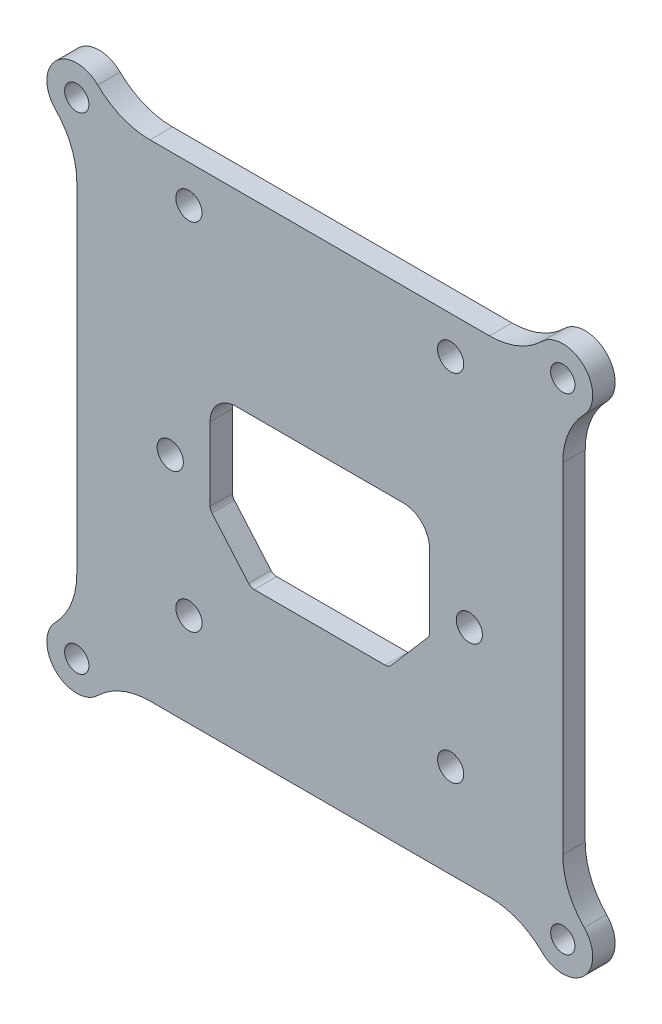
SolidWorks part; units mm, degrees
material "ABS"
ref_plane "Спереди" through (0, 0, 0) normal (0, 0, 1) x (1, 0, 0)
ref_plane "Сверху" through (0, 0, 0) normal (0, 1, 0) x (1, 0, 0)
ref_plane "Справа" through (0, 0, 0) normal (1, 0, 0) x (0, 0, -1)
sketch "Эскиз1" plane through (0, 0, 0) normal (0, 0, 1) x (1, 0, 0)
  line L1 (-32.5, -32.5) -> (32.5, -32.5)
  line L2 (-32.5, -32.5) -> (-32.5, 32.5)
  line L3 (-32.5, 32.5) -> (32.5, 32.5)
  line L4 (32.5, -32.5) -> (32.5, 32.5)
  line L5 (-32.5, -32.5) -> (32.5, 32.5) construction
  line L6 (-32.5, 32.5) -> (32.5, -32.5) construction
  circle A0 centre (-32.5, 32.5) radius 1.625
  arc A1 (-28.5, 32.5) -> (-32.5, 28.5) centre (-32.5, 32.5) ccw
  circle A2 centre (32.5, 32.5) radius 1.625
  arc A3 (32.5, 28.5) -> (28.5, 32.5) centre (32.5, 32.5) ccw
  circle A4 centre (32.5, -32.5) radius 1.625
  arc A5 (28.5, -32.5) -> (32.5, -28.5) centre (32.5, -32.5) ccw
  circle A6 centre (-32.5, -32.5) radius 1.625
  arc A7 (-32.5, -28.5) -> (-28.5, -32.5) centre (-32.5, -32.5) ccw
  point P0 (0, 0)
  point P20 (0, 0)
  dimension "D2" = 3.25
  dimension "D3" = 8
  dimension "D1" = 65
  dimension "D4" = 4
extrude "Бобышка-Вытянуть1" add sketch "Эскиз1" along normal blind 3 contours A6 L1 A4 L4 A2 L3 A0 L2 | L3 A1 L2 A0 | L4 A3 L3 A2 | L1 A5 L4 A4 | L2 A7 L1 A6
fillet "Скругление1" radius 10 8 edges at (-28.5, -32.5, 1.5) (-32.5, -28.5, 1.5) (-28.5, 32.5, 1.5) (-32.5, 28.5, 1.5) (28.5, 32.5, 1.5) (32.5, 28.5, 1.5) (32.5, -28.5, 1.5) (28.5, -32.5, 1.5)
sketch "Эскиз3" plane through (0, 0, 0) normal (0, 0, -1) x (-1, 0, 0)
  line L0 (0, 32.5) -> (0, -32.5) construction
  line L1 (22.702, 32.5) -> (-22.702, 32.5) construction
  line L2 (22.702, -32.5) -> (-22.702, -32.5) construction
  line L3 (-31.8936, 27.5) -> (26.7306, 27.5) construction
  circle A0 centre (-17.5, 27.5) radius 1.75
  circle A1 centre (17.5, 27.5) radius 1.75
  dimension "D1" = 3.5
  dimension "D2" = 17.5
  dimension "D3" = 27.5
extrude "Вырез-Вытянуть1" cut sketch "Эскиз3" against normal blind 10
sketch "Эскиз4" plane through (0, 0, 0) normal (0, 0, -1) x (-1, 0, 0)
  line L0 (0, 32.5) -> (0, -32.5) construction
  line L1 (22.702, 32.5) -> (-22.702, 32.5) construction
  line L2 (22.702, -32.5) -> (-22.702, -32.5) construction
  line L3 (-25.8899, -2.6153) -> (17.0132, -2.6153) construction
  circle A0 centre (-20, -2.6153) radius 1.75
  circle A1 centre (20, -2.6153) radius 1.75
  dimension "D1" = 3.5
  dimension "D2" = 20
extrude "Вырез-Вытянуть2" cut sketch "Эскиз4" against normal blind 10
sketch "Эскиз5" plane through (0, 0, 3) normal (0, 0, 1) x (1, 0, 0)
  line L0 (0, 32.5) -> (0, -32.5) construction
  line L1 (-22.702, 32.5) -> (22.702, 32.5) construction
  line L2 (-22.702, -32.5) -> (22.702, -32.5) construction
  line L3 (-29.8417, -20) -> (25.7956, -20) construction
  circle A0 centre (-17.5, -20) radius 1.75
  circle A1 centre (17.5, -20) radius 1.75
  dimension "D1" = 3.5
  dimension "D2" = 17.5
  dimension "D3" = 20
extrude "Вырез-Вытянуть3" cut sketch "Эскиз5" against normal blind 10
sketch "Эскиз6" plane through (0, 0, 3) normal (0, 0, 1) x (1, 0, 0)
  line L0 (-0.85, -3.2653) -> (0.85, -3.2653)
  line L1 (-0.95, -7.1653) -> (-0.95, -3.3653)
  line L2 (0.95, -3.3653) -> (0.95, -7.1653)
  line L3 (0.85, -7.2653) -> (-0.85, -7.2653)
  line L4 (-6.3, -2.0653) -> (-8, -2.0653)
  line L5 (-6.2, 1.8347) -> (-6.2, -1.9653)
  line L6 (-8.1, -1.9653) -> (-8.1, 1.8347)
  line L7 (-8, 1.9347) -> (-6.3, 1.9347)
  line L8 (12.45, 5.4347) -> (-12.45, 5.4347)
  line L9 (-12.45, -6.5653) -> (-12.45, 5.4347)
  line L10 (12.45, -6.5653) -> (12.45, 5.4347)
  line L11 (-12.45, -6.5653) -> (-7.5, -10.6653)
  line L12 (7.5, -10.6653) -> (12.45, -6.5653)
  line L13 (-7.5, -10.6653) -> (7.5, -10.6653)
  line L14 (8, -2.0653) -> (6.3, -2.0653)
  line L15 (8.1, 1.8347) -> (8.1, -1.9653)
  line L16 (6.2, -1.9653) -> (6.2, 1.8347)
  line L17 (6.3, 1.9347) -> (8, 1.9347)
  line L18 (-12.8717, 6.3554) -> (-22.1648, 1.8918)
  line L19 (-12.0348, 6.7574) -> (-12.8717, 6.3554)
  line L20 (-10, 7.7347) -> (-12.0348, 6.7574)
  line L21 (-10, 7.7347) -> (10, 7.7347)
  line L22 (10, 7.7347) -> (12.0348, 6.7574)
  line L23 (12.0348, 6.7574) -> (12.8717, 6.3554)
  line L24 (12.8717, 6.3554) -> (22.1648, 1.8918)
  line L25 (-22.1648, -7.1223) -> (-10, -12.9653)
  line L26 (-10, -12.9653) -> (10, -12.9653)
  line L27 (10, -12.9653) -> (22.1648, -7.1223)
  line L28 (11.17, 6.8847) -> (-11.17, 6.8847)
  line L29 (14.17, -5.9296) -> (14.17, 3.8847)
  line L30 (9.1496, -11.9416) -> (14.0488, -6.2559)
  line L31 (-8.7708, -12.1153) -> (8.7708, -12.1153)
  line L32 (-14.0488, -6.2559) -> (-9.1496, -11.9416)
  line L33 (-14.17, 3.8847) -> (-14.17, -5.9296)
  line L34 (-14.17, 3.8847) -> (-14.17, -5.9296)
  line L35 (-14.0488, -6.2559) -> (-9.1496, -11.9416)
  line L36 (-8.7708, -12.1153) -> (8.7708, -12.1153)
  line L37 (9.1496, -11.9416) -> (14.0488, -6.2559)
  line L38 (14.17, -5.9296) -> (14.17, 3.8847)
  line L39 (11.17, 6.8847) -> (-11.17, 6.8847)
  line L40 (10, -12.9653) -> (22.1648, -7.1223)
  line L41 (-10, -12.9653) -> (10, -12.9653)
  line L42 (-22.1648, -7.1223) -> (-10, -12.9653)
  line L43 (12.8717, 6.3554) -> (22.1648, 1.8918)
  line L44 (12.0348, 6.7574) -> (12.8717, 6.3554)
  line L45 (10, 7.7347) -> (12.0348, 6.7574)
  line L46 (-10, 7.7347) -> (10, 7.7347)
  line L47 (-10, 7.7347) -> (-12.0348, 6.7574)
  line L48 (-12.0348, 6.7574) -> (-12.8717, 6.3554)
  line L49 (-12.8717, 6.3554) -> (-22.1648, 1.8918)
  line L50 (6.3, 1.9347) -> (8, 1.9347)
  line L51 (6.2, -1.9653) -> (6.2, 1.8347)
  line L52 (8.1, 1.8347) -> (8.1, -1.9653)
  line L53 (8, -2.0653) -> (6.3, -2.0653)
  line L54 (-7.5, -10.6653) -> (7.5, -10.6653)
  line L55 (7.5, -10.6653) -> (12.45, -6.5653)
  line L56 (-12.45, -6.5653) -> (-7.5, -10.6653)
  line L57 (12.45, -6.5653) -> (12.45, 5.4347)
  line L58 (-12.45, -6.5653) -> (-12.45, 5.4347)
  line L59 (12.45, 5.4347) -> (-12.45, 5.4347)
  line L60 (-8, 1.9347) -> (-6.3, 1.9347)
  line L61 (-8.1, -1.9653) -> (-8.1, 1.8347)
  line L62 (-6.2, 1.8347) -> (-6.2, -1.9653)
  line L63 (-6.3, -2.0653) -> (-8, -2.0653)
  line L64 (0.85, -7.2653) -> (-0.85, -7.2653)
  line L65 (0.95, -3.3653) -> (0.95, -7.1653)
  line L66 (-0.95, -7.1653) -> (-0.95, -3.3653)
  line L67 (-0.85, -3.2653) -> (0.85, -3.2653)
  line L68 (-14.67, 3.8847) -> (-14.67, -5.9296)
  line L69 (-14.4276, -6.5823) -> (-9.5284, -12.268)
  line L70 (-8.7708, -12.6153) -> (8.7708, -12.6153)
  line L71 (9.5284, -12.268) -> (14.4276, -6.5823)
  line L72 (14.67, -5.9296) -> (14.67, 3.8847)
  line L73 (11.17, 7.3847) -> (-11.17, 7.3847)
  arc A0 (-0.85, -3.2653) -> (-0.95, -3.3653) centre (-0.85, -3.3653) ccw
  arc A1 (0.95, -3.3653) -> (0.85, -3.2653) centre (0.85, -3.3653) ccw
  arc A2 (-0.95, -7.1653) -> (-0.85, -7.2653) centre (-0.85, -7.1653) ccw
  arc A3 (0.85, -7.2653) -> (0.95, -7.1653) centre (0.85, -7.1653) ccw
  arc A4 (-6.3, -2.0653) -> (-6.2, -1.9653) centre (-6.3, -1.9653) ccw
  arc A5 (-8.1, -1.9653) -> (-8, -2.0653) centre (-8, -1.9653) ccw
  arc A6 (-6.2, 1.8347) -> (-6.3, 1.9347) centre (-6.3, 1.8347) ccw
  arc A7 (-8, 1.9347) -> (-8.1, 1.8347) centre (-8, 1.8347) ccw
  arc A8 (8, -2.0653) -> (8.1, -1.9653) centre (8, -1.9653) ccw
  arc A9 (6.2, -1.9653) -> (6.3, -2.0653) centre (6.3, -1.9653) ccw
  arc A10 (8.1, 1.8347) -> (8, 1.9347) centre (8, 1.8347) ccw
  arc A11 (6.3, 1.9347) -> (6.2, 1.8347) centre (6.3, 1.8347) ccw
  arc A12 (-22.1648, 1.8918) -> (-22.1648, -7.1223) centre (-20, -2.6153) ccw
  arc A13 (22.1648, -7.1223) -> (22.1648, 1.8918) centre (20, -2.6153) ccw
  arc A14 (-12.8717, 6.3554) -> (-14.17, 3.8847) centre (-11.17, 3.8847) ccw
  arc A15 (-12.0348, 6.7574) -> (-12.8717, 6.3554) centre (-11.17, 3.8847) ccw
  arc A16 (-11.17, 6.8847) -> (-12.0348, 6.7574) centre (-11.17, 3.8847) ccw
  arc A17 (12.0348, 6.7574) -> (11.17, 6.8847) centre (11.17, 3.8847) ccw
  arc A18 (12.8717, 6.3554) -> (12.0348, 6.7574) centre (11.17, 3.8847) ccw
  arc A19 (14.17, 3.8847) -> (12.8717, 6.3554) centre (11.17, 3.8847) ccw
  arc A20 (14.0488, -6.2559) -> (14.17, -5.9296) centre (13.67, -5.9296) ccw
  arc A21 (8.7708, -12.1153) -> (9.1496, -11.9416) centre (8.7708, -11.6153) ccw
  arc A22 (-9.1496, -11.9416) -> (-8.7708, -12.1153) centre (-8.7708, -11.6153) ccw
  arc A23 (-14.17, -5.9296) -> (-14.0488, -6.2559) centre (-13.67, -5.9296) ccw
  circle A24 centre (20, -2.6153) radius 1.5
  circle A25 centre (-20, -2.6153) radius 1.5
  circle A26 centre (-20, -2.6153) radius 1.5
  circle A27 centre (20, -2.6153) radius 1.5
  arc A28 (-14.17, -5.9296) -> (-14.0488, -6.2559) centre (-13.67, -5.9296) ccw
  arc A29 (-9.1496, -11.9416) -> (-8.7708, -12.1153) centre (-8.7708, -11.6153) ccw
  arc A30 (8.7708, -12.1153) -> (9.1496, -11.9416) centre (8.7708, -11.6153) ccw
  arc A31 (14.0488, -6.2559) -> (14.17, -5.9296) centre (13.67, -5.9296) ccw
  arc A32 (14.17, 3.8847) -> (12.8717, 6.3554) centre (11.17, 3.8847) ccw
  arc A33 (12.8717, 6.3554) -> (12.0348, 6.7574) centre (11.17, 3.8847) ccw
  arc A34 (12.0348, 6.7574) -> (11.17, 6.8847) centre (11.17, 3.8847) ccw
  arc A35 (-11.17, 6.8847) -> (-12.0348, 6.7574) centre (-11.17, 3.8847) ccw
  arc A36 (-12.0348, 6.7574) -> (-12.8717, 6.3554) centre (-11.17, 3.8847) ccw
  arc A37 (-12.8717, 6.3554) -> (-14.17, 3.8847) centre (-11.17, 3.8847) ccw
  arc A38 (22.1648, -7.1223) -> (22.1648, 1.8918) centre (20, -2.6153) ccw
  arc A39 (-22.1648, 1.8918) -> (-22.1648, -7.1223) centre (-20, -2.6153) ccw
  arc A40 (6.3, 1.9347) -> (6.2, 1.8347) centre (6.3, 1.8347) ccw
  arc A41 (8.1, 1.8347) -> (8, 1.9347) centre (8, 1.8347) ccw
  arc A42 (6.2, -1.9653) -> (6.3, -2.0653) centre (6.3, -1.9653) ccw
  arc A43 (8, -2.0653) -> (8.1, -1.9653) centre (8, -1.9653) ccw
  arc A44 (-8, 1.9347) -> (-8.1, 1.8347) centre (-8, 1.8347) ccw
  arc A45 (-6.2, 1.8347) -> (-6.3, 1.9347) centre (-6.3, 1.8347) ccw
  arc A46 (-8.1, -1.9653) -> (-8, -2.0653) centre (-8, -1.9653) ccw
  arc A47 (-6.3, -2.0653) -> (-6.2, -1.9653) centre (-6.3, -1.9653) ccw
  arc A48 (0.85, -7.2653) -> (0.95, -7.1653) centre (0.85, -7.1653) ccw
  arc A49 (-0.95, -7.1653) -> (-0.85, -7.2653) centre (-0.85, -7.1653) ccw
  arc A50 (0.95, -3.3653) -> (0.85, -3.2653) centre (0.85, -3.3653) ccw
  arc A51 (-0.85, -3.2653) -> (-0.95, -3.3653) centre (-0.85, -3.3653) ccw
  arc A52 (-13.1553, 6.7672) -> (-14.67, 3.8847) centre (-11.17, 3.8847) ccw
  arc A53 (-14.67, -5.9296) -> (-14.4276, -6.5823) centre (-13.67, -5.9296) ccw
  arc A54 (-9.5284, -12.268) -> (-8.7708, -12.6153) centre (-8.7708, -11.6153) ccw
  arc A55 (8.7708, -12.6153) -> (9.5284, -12.268) centre (8.7708, -11.6153) ccw
  arc A56 (14.4276, -6.5823) -> (14.67, -5.9296) centre (13.67, -5.9296) ccw
  arc A57 (14.67, 3.8847) -> (13.1553, 6.7672) centre (11.17, 3.8847) ccw
  arc A58 (12.179, 7.2362) -> (11.17, 7.3847) centre (11.17, 3.8847) ccw
  arc A59 (-11.17, 7.3847) -> (-12.179, 7.2362) centre (-11.17, 3.8847) ccw
  spline S0 degree 2 poles (-12.179, 7.2362) (-12.7065, 7.0801) (-13.1553, 6.7672) knots 0 0 0 1 1 1
  spline S1 degree 2 poles (12.179, 7.2362) (12.7082, 7.085) (13.1553, 6.7672) knots 0 0 0 1 1 1
  dimension "D1" = 0.5
extrude "Вырез-Вытянуть5" cut sketch "Эскиз6" against normal blind 10 contours L72 A57 L43 A32 L38 A31 L37 A30 L36 A29 L35 A28 L34 A37 L49 A52 L68 A53 L69 A54 L70 A55 L71 A56 | S1 A58 L73 L45 A33 L43 A57 | A35 L39 A34 L45 L73 L47 | A59 S0 A52 L49 A36 L47 L73
